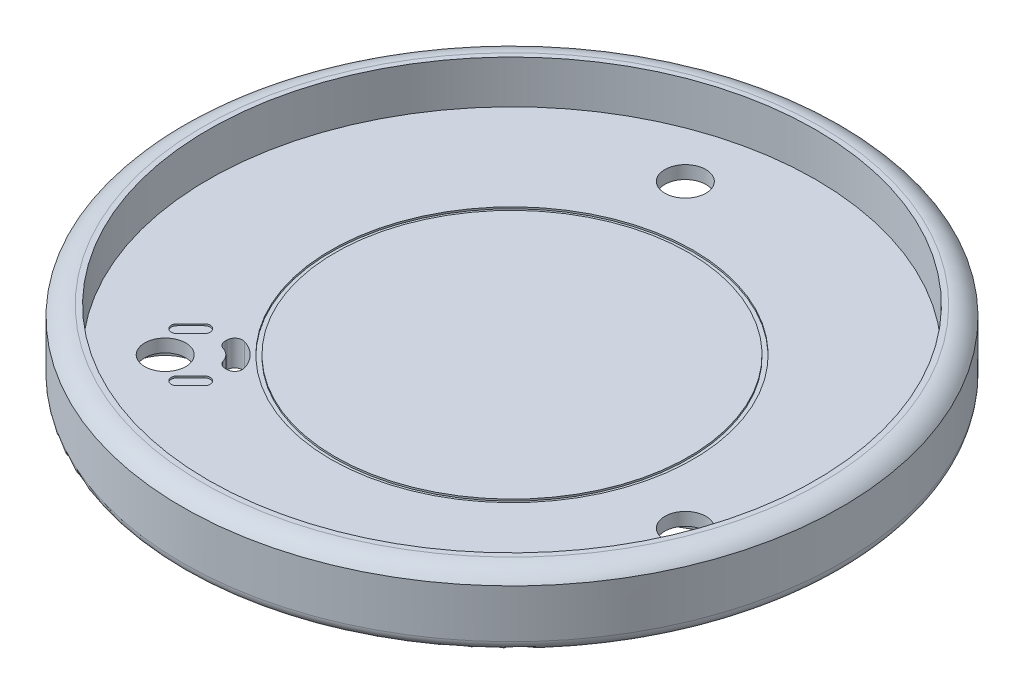
SolidWorks part; units mm, degrees
ref_plane "前视基准面" through (0, 0, 0) normal (0, 0, 1) x (1, 0, 0)
ref_plane "上视基准面" through (0, 0, 0) normal (0, 1, 0) x (1, 0, 0)
ref_plane "右视基准面" through (0, 0, 0) normal (1, 0, 0) x (0, 0, -1)
sketch "草图1" plane through (0, 0, 0) normal (0, 1, 0) x (1, 0, 0)
  circle A0 centre (0, 0) radius 35.2
  circle A1 centre (0, 0) radius 20.5 construction
  dimension "D1" = 70.4
  dimension "D2" = 41
extrude "凸台-拉伸1" add sketch "草图1" along normal blind 3
sketch "草图3" plane through (0, 0, 0) normal (0, -1, 0) x (1, 0, 0)
  circle A0 centre (0, 0) radius 38.2
  circle A1 centre (0, 0) radius 35.2 construction
  circle A2 centre (0, 0) radius 35.2
  dimension "D1" = 3
extrude "凸台-拉伸2" add sketch "草图3" against normal blind 8
sketch "草图4" plane through (0, 3, 0) normal (0, 1, 0) x (1, 0, 0)
  line L0 (-37.8336, 0) -> (34.4444, 0) construction
  line L1 (0, 37.4001) -> (0, -32.3556) construction
  circle A0 centre (0, 0) radius 20.5
  circle A1 centre (0, 0) radius 21
  dimension "D1" = 41
  dimension "D2" = 42
extrude "切除-拉伸1" cut sketch "草图4" against normal blind 0.2
sketch "草图5" plane through (0, 0, 0) normal (1, 0, 0) x (0, 0, -1)
  line L0 (38.2, 6.8) -> (38.2, 8)
  line L2 (38.2, 8) -> (35.8, 8)
  line L3 (35.2, 8) -> (-35.2, 8) construction
  line L4 (0, 0) -> (0, 12.9368)
  arc A0 (35.8, 8) -> (38.2, 6.8) centre (35.8, 5) cw
  dimension "D1" = 1.2
  dimension "D2" = 2.4
revolve "切除-旋转1" cut sketch "草图5" angle 360 about L4
fillet "圆角2" radius 1.2 1 edges at (0, 0, -38.2)
sketch "草图6" plane through (0, 0, 0) normal (0, -1, 0) x (1, 0, 0)
  line L0 (-29.5028, 0) -> (27.9284, 0) construction
  line L1 (0, 23.6501) -> (0, -22.1442) construction
  line L2 (-26, 23.2) -> (-23.8509, 18.3731)
  line L3 (-24, 26) -> (-18, 26)
  line L4 (-26, 24) -> (-26, 19)
  line L5 (-20.1967, 16) -> (-18, 16)
  line L6 (-16, 20.1967) -> (-16, 18)
  line L7 (-23.2, 26) -> (-18.3731, 23.8509)
  line L8 (33.0918, 10.9167) -> (27.837, 11.469)
  line L9 (33.7846, 10.5167) -> (29.4545, 13.0167)
  line L10 (34.5167, 7.7846) -> (31.5167, 2.5885)
  line L11 (34.1167, 7.0918) -> (29.842, 3.9861)
  line L12 (25.4909, 3.758) -> (23.5885, 4.8564)
  line L13 (23.9548, 9.4909) -> (22.8564, 7.5885)
  line L14 (-7.0918, -34.1167) -> (-3.9861, -29.842)
  line L15 (-7.7846, -34.5167) -> (-3.4545, -32.0167)
  line L16 (-10.5167, -33.7846) -> (-13.5167, -28.5885)
  line L17 (-10.9167, -33.0918) -> (-11.469, -27.837)
  line L18 (-9.4909, -23.9548) -> (-7.5885, -22.8564)
  line L19 (-3.758, -25.4909) -> (-4.8564, -23.5885)
  arc A0 (-26, 24) -> (-24, 26) centre (-24, 24) cw
  arc A1 (-18, 16) -> (-16, 18) centre (-18, 18) ccw
  arc A2 (-16, 20.1967) -> (-18.3731, 23.8509) centre (-20, 20.1967) ccw
  arc A3 (-23.8509, 18.3731) -> (-20.1967, 16) centre (-20.1967, 20) ccw
  arc A4 (33.7846, 10.5167) -> (34.5167, 7.7846) centre (32.7846, 8.7846) cw
  arc A5 (25.4909, 3.758) -> (29.842, 3.9861) centre (27.4909, 7.2221) ccw
  arc A6 (22.8564, 7.5885) -> (23.5885, 4.8564) centre (24.5885, 6.5885) ccw
  arc A7 (27.837, 11.469) -> (23.9548, 9.4909) centre (27.4189, 7.4909) ccw
  arc A8 (-7.7846, -34.5167) -> (-10.5167, -33.7846) centre (-8.7846, -32.7846) cw
  arc A9 (-9.4909, -23.9548) -> (-11.469, -27.837) centre (-7.4909, -27.4189) ccw
  arc A10 (-4.8564, -23.5885) -> (-7.5885, -22.8564) centre (-6.5885, -24.5885) ccw
  arc A11 (-3.9861, -29.842) -> (-3.758, -25.4909) centre (-7.2221, -27.4909) ccw
  point P11 (-26, 26)
  point P18 (-16, 16)
  point P58 (0, 0)
  dimension "D5" = 2
  dimension "D10" = 2
  dimension "D3" = 4
  dimension "D1" = 16
  dimension "D2" = 16
  dimension "D4" = 10
  dimension "D6" = 24
  dimension "D7" = 24
  dimension "D8" = 0.8
  dimension "D9" = 0.8
  dimension "D11" = 10
  dimension "D12" = 3
extrude "切除-拉伸2" cut sketch "草图6" against normal blind 1.5 contours L14 A11 L19 A10 L18 A9 L17 L16 A8 L15 | L8 A7 L13 A6 L12 A5 L11 L10 A4 L9 | L2 A3 L5 A1 L6 A2 L7 L3 A0 L4
sketch "草图7" plane through (0, 0, 0) normal (0, -1, 0) x (1, 0, 0)
  line L0 (0, 0) -> (-25.4142, 25.4142) construction
  line L1 (-18, 15.0335) -> (-18, 15.2432)
  line L2 (-15.0335, 18) -> (-15.2432, 18)
  arc A0 (-24, 26) -> (-26, 24) centre (-24, 24) ccw construction
  arc A3 (-18, 16) -> (-16, 18) centre (-18, 18) ccw construction
  arc A4 (-17.3793, 16.0988) -> (-16.0988, 17.3793) centre (-18, 18) ccw
  arc A5 (-16.8387, 14.1723) -> (-14.1723, 16.8387) centre (-18, 18) ccw
  arc A6 (-18, 16) -> (-16, 18) centre (-18, 18) ccw construction
  arc A7 (-18, 15.2432) -> (-17.3793, 16.0988) centre (-17.1, 15.2432) cw
  arc A8 (-18, 14) -> (-14, 18) centre (-18, 18) ccw construction
  arc A9 (-18, 15.0335) -> (-16.8387, 14.1723) centre (-17.1, 15.0335) ccw
  arc A10 (-14.1723, 16.8387) -> (-15.0335, 18) centre (-15.0335, 17.1) ccw
  arc A11 (-15.2432, 18) -> (-16.0988, 17.3793) centre (-15.2432, 17.1) ccw
  dimension "D2" = 0.9
  dimension "D1" = 2
extrude "切除-拉伸3" cut sketch "草图7" against normal blind 10
sketch "草图8" plane through (0, 3, 0) normal (0, 1, 0) x (1, 0, 0)
  line L0 (0, 0) -> (-24.3102, -24.3102) construction
  line L1 (-16.7808, -22.0134) -> (-15.2252, -20.4578) construction
  line L2 (-17.2758, -21.5184) -> (-15.7201, -19.9628)
  line L3 (-16.2858, -22.5084) -> (-14.7302, -20.9527)
  line L4 (-22.0134, -16.7808) -> (-20.4578, -15.2252) construction
  line L5 (-21.5184, -17.2758) -> (-19.9628, -15.7201)
  line L6 (-22.5084, -16.2858) -> (-20.9527, -14.7302)
  arc A0 (-17.2758, -21.5184) -> (-16.2858, -22.5084) centre (-16.7808, -22.0134) ccw
  arc A1 (-14.7302, -20.9527) -> (-15.7201, -19.9628) centre (-15.2252, -20.4578) ccw
  arc A2 (-16.0988, -17.3793) -> (-17.3793, -16.0988) centre (-18, -18) ccw construction
  arc A3 (-16.0988, -17.3793) -> (-17.3793, -16.0988) centre (-18, -18) ccw
  arc A4 (-21.5184, -17.2758) -> (-22.5084, -16.2858) centre (-22.0134, -16.7808) cw
  arc A5 (-20.9527, -14.7302) -> (-19.9628, -15.7201) centre (-20.4578, -15.2252) cw
  point P5 (-16.003, -21.2356)
  point P16 (-21.2356, -16.003)
  dimension "D2" = 0.7
  dimension "D1" = 2.2
  dimension "D3" = 3
  dimension "D4" = 3.2
extrude "切除-拉伸4" cut sketch "草图8" against normal blind 0.2 contours A5 L6 A4 L5 | L3 A1 L2 A0
sketch "草图9" plane through (0, 3, 0) normal (0, 1, 0) x (1, 0, 0)
  line L0 (-20, -20.1967) -> (-20.1967, -20)
  line L1 (0, 0) -> (-20.0984, -20.0984) construction
  circle A0 centre (-20.0984, -20.0984) radius 2.38
  circle A1 centre (-7.3565, 27.4549) radius 2.38
  circle A2 centre (27.4549, -7.3565) radius 2.38
  dimension "D1" = 4.76
  dimension "D3" = 28.4234
  dimension "D2" = 3
extrude "切除-拉伸5" cut sketch "草图9" against normal blind 10
sketch "草图10" plane through (0, 0, 0) normal (0, -1, 0) x (1, 0, 0)
  line L0 (0, 0) -> (-15.1716, 15.1716) construction
  line L1 (-21.7279, -6.5563) -> (6.5563, 21.7279) construction
  arc A0 (-16.8387, 14.1723) -> (-14.1723, 16.8387) centre (-18, 18) ccw construction
  text T0 "<b>07</b>" font "JetBrains Mono" height 9
  point P10 (-7.5858, 7.5858)
  dimension "D1" = 20
  dimension "D2" = 40
extrude "切除-拉伸6" cut sketch "草图10" against normal blind 0.8
